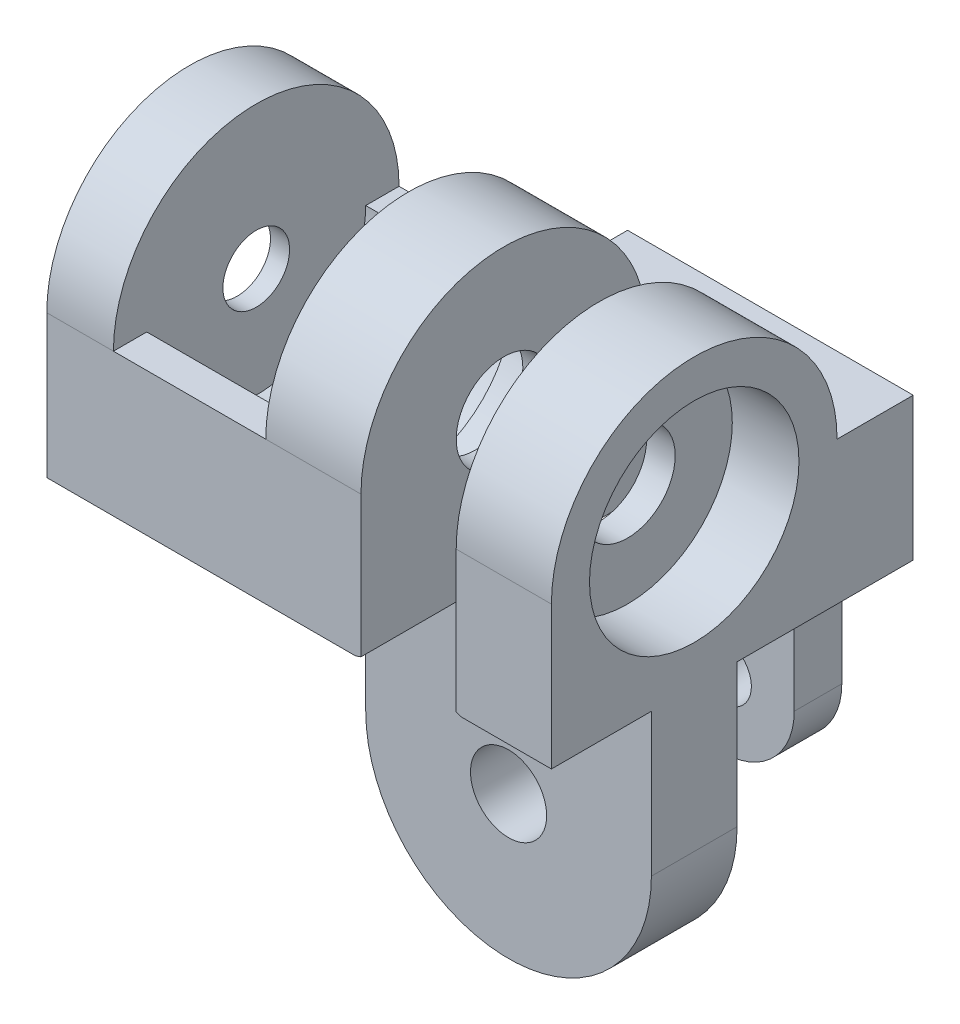
SolidWorks part; units mm, degrees
ref_plane "Front Plane" through (0, 0, 0) normal (0, 0, 1) x (1, 0, 0)
ref_plane "Top Plane" through (0, 0, 0) normal (0, 1, 0) x (1, 0, 0)
ref_plane "Right Plane" through (0, 0, 0) normal (1, 0, 0) x (0, 0, -1)
sketch "Sketch1" plane through (0, 0, 0) normal (0, 1, 0) x (1, 0, 0)
  circle A0 centre (0, 0) radius 15
  dimension "D1" = 30
extrude "Boss-Extrude1" add sketch "Sketch1" along normal blind 30
sketch "Sketch8" plane through (0, 30, 0) normal (0, 1, 0) x (1, 0, 0)
  line L0 (-16.5, 0) -> (16.5, 0) construction
  line L1 (15, 0) -> (-15, 0)
  line L2 (15, 0) -> (15, -15)
  line L3 (15, -15) -> (-15, -15)
  line L4 (-15, 0) -> (-15, -15)
  circle A0 centre (0, 0) radius 15 construction
  dimension "D1" = 15
  dimension "D2" = 30
revolve "Revolve1" add sketch "Sketch8" angle 180 about L1
sketch "Sketch9" plane through (0, 30, 0) normal (0, -1, 0) x (1, 0, 0)
  line L1 (15, 15) -> (-15, 15)
  line L2 (15, 15) -> (15, -15)
  line L3 (15, -15) -> (-15, -15)
  line L4 (-15, 15) -> (-15, -15)
extrude "Boss-Extrude3" add sketch "Sketch9" along normal blind 15
sketch "Sketch10" plane through (15, 0, 0) normal (1, 0, 0) x (0, 0, -1)
  circle A0 centre (0, 30) radius 5
  dimension "D1" = 10
extrude "Cut-Extrude1" cut sketch "Sketch10" against normal blind 30
ref_plane "Plane1" through (5, 0, 0) normal (1, 0, 0) x (0, 0, -1)
sketch "Sketch13" plane through (5, 0, 0) normal (1, 0, 0) x (0, 0, -1)
  line L0 (0, 16.5) -> (0, -16.5) construction
  line L1 (15, 15) -> (0, 15) construction
  circle A0 centre (0, 30) radius 16
  dimension "D1" = 32
  dimension "D2" = 15
extrude "Cut-Extrude2" cut sketch "Sketch13" against normal blind 10
sketch "Sketch14" plane through (0, 0, 15) normal (0, 0, 1) x (1, 0, 0)
  line L0 (5, -16.5) -> (5, 16.5) construction
  line L1 (-5, 30) -> (5, 30)
  line L2 (-5, 30) -> (-5, 15)
  line L3 (-5, 15) -> (5, 15)
  line L4 (5, 30) -> (5, 15)
  line L5 (0, 15) -> (15, 15) construction
extrude "Cut-Extrude3" cut sketch "Sketch14" against normal blind 67
sketch "Sketch15" plane through (-15, 0, 0) normal (-1, 0, 0) x (0, 0, 1)
  circle A0 centre (0, 30) radius 5 construction
  circle A1 centre (0, 30) radius 5
  circle A2 centre (0, 30) radius 11
  dimension "D1" = 22
extrude "Cut-Extrude4" cut sketch "Sketch15" against normal blind 7
sketch "Sketch16" plane through (15, 0, 0) normal (1, 0, 0) x (0, 0, -1)
  circle A0 centre (0, 30) radius 5 construction
  circle A1 centre (0, 30) radius 5
  circle A2 centre (0, 30) radius 11
  dimension "D1" = 22
extrude "Cut-Extrude5" cut sketch "Sketch16" against normal blind 7
ref_plane "Plane2" through (-31, 0, 0) normal (-1, 0, 0) x (0, 0, 1)
sketch "Sketch17" plane through (-31, 0, 0) normal (-1, 0, 0) x (0, 0, 1)
  line L0 (-15, 30) -> (-15, 15)
  line L1 (-15, 15) -> (0, 15)
  line L2 (0, 15) -> (15, 15)
  line L3 (15, 15) -> (15, 30)
  circle A2 centre (0, 30) radius 3.5
  circle A3 centre (0, 30) radius 11 construction
  circle A4 centre (0, 30) radius 8
  circle A5 centre (0, 30) radius 15
  arc A6 (-15, 30) -> (0, 15) centre (0, 30) ccw
  arc A7 (15, 30) -> (0, 15) centre (0, 30) cw
  dimension "D1" = 7
  dimension "D2" = 16
extrude "Boss-Extrude4" add sketch "Sketch17" along normal blind 2 separate body contours A4 A2 | A5 A4 | A5 L0 L1 | A5 L2 L3
sketch "Sketch18" plane through (-33, 0, 0) normal (-1, 0, 0) x (0, 0, 1)
  line L0 (8.5, 30) -> (8.5, 15)
  line L1 (-15, 15) -> (15, 15) construction
  line L2 (8.5, 15) -> (-8.5, 15)
  line L3 (-8.5, 15) -> (-8.5, 30)
  circle A2 centre (0, 30) radius 8.5
  dimension "D1" = 17
extrude "Boss-Extrude5" add sketch "Sketch18" along normal blind 5
sketch "Sketch20" plane through (-15, 0, 0) normal (-1, 0, 0) x (0, 0, 1)
  line L0 (-11.5, 30) -> (-15, 30)
  line L1 (-15, 30) -> (-15, 15)
  line L2 (-15, 15) -> (15, 15)
  line L3 (15, 15) -> (14.1421, 15) construction
  line L4 (-15, 15) -> (-8.5, 15) construction
  line L5 (15, 15) -> (15, 30)
  line L6 (15, 15) -> (15, 30) construction
  line L7 (15, 30) -> (11.5, 30)
  circle A0 centre (0, 30) radius 11.5
  line M4 (-15, 30) -> (-15, 15)
  line M5 (-15, 15) -> (0, 15)
  line M6 (0, 15) -> (15, 15)
  line M7 (15, 15) -> (15, 30)
  dimension "D1" = 23
extrude "Boss-Extrude6" add sketch "Sketch20" along normal blind 16 contours A0 L0 L7 M4 M5 M6 M7
sketch "Sketch21" plane through (0, 15, 0) normal (0, -1, 0) x (1, 0, 0)
  line L1 (15, 15) -> (-38, 15)
  line L2 (15, 15) -> (15, -15)
  line L3 (15, -15) -> (-38, -15)
  line L4 (-38, 15) -> (-38, -15)
extrude "Cut-Extrude7" cut sketch "Sketch21" along normal blind 20
ref_plane "Plane3" through (0, 0, 0) normal (0, -1, 0) x (-1, 0, 0)
sketch "Sketch23" plane through (0, 0, 0) normal (0, -1, 0) x (-1, 0, 0)
  line L0 (-15, -4.5) -> (0, -4.5)
  line L1 (-15, -4.5) -> (-15, 4.5)
  line L2 (0, -4.5) -> (0, 4.5)
  line L3 (-15, 4.5) -> (0, 4.5)
  line L4 (-15, 15) -> (-15, -15) construction
  line L5 (0, 16.5) -> (0, -16.5) construction
  line L6 (-16.5, 0) -> (16.5, 0) construction
  dimension "D1" = 9
  dimension "D2" = 4.5
revolve "Revolve2" add sketch "Sketch23" angle 360 about L2
sketch "Sketch24" plane through (0, 15, 0) normal (0, -1, 0) x (1, 0, 0)
  line L1 (-15, 4.5) -> (15, 4.5)
  line L2 (-15, 4.5) -> (-15, -4.5)
  line L3 (-15, -4.5) -> (15, -4.5)
  line L4 (15, 4.5) -> (15, -4.5)
extrude "Boss-Extrude7" add sketch "Sketch24" along normal blind 15
sketch "Sketch25" plane through (0, 0, 4.5) normal (0, 0, 1) x (1, 0, 0)
  circle A0 centre (0, 0) radius 4
  dimension "D1" = 8
extrude "Cut-Extrude8" cut sketch "Sketch25" against normal blind 15
sketch "Sketch26" plane through (0, 0, -15) normal (0, 0, -1) x (-1, 0, 0)
  line L0 (-16.5, 0) -> (16.5, 0) construction
  line L1 (-15, 30) -> (15, 30)
  line L2 (-15, 30) -> (-15, 15)
  line L3 (-15, 15) -> (-12.5, 15)
  line L4 (15, 30) -> (15, 15)
  line L6 (-7.5, 10) -> (-7.5, 0)
  line L7 (-7.5, 0) -> (7.5, 0)
  line L8 (7.5, 10) -> (7.5, 0)
  line L9 (-5, 15) -> (-15, 15) construction
  line L10 (12.5, 15) -> (15, 15)
  line L11 (38, 15) -> (5, 15) construction
  line L12 (15, 30) -> (15, 45) construction
  circle A0 centre (0, 0) radius 7.5
  circle A1 centre (0, 0) radius 3
  arc A2 (-7.5, 10) -> (-12.5, 15) centre (-12.5, 10) ccw
  arc A3 (12.5, 15) -> (7.5, 10) centre (12.5, 10) ccw
  line M13 (-15, 15) -> (-5, 15)
  line M14 (-5, 15) -> (-5, 30)
  line M15 (-5, 30) -> (-15, 30)
  line M16 (-15, 30) -> (-15, 15)
  dimension "D1" = 6
  dimension "D2" = 15
  dimension "D3" = 5
  dimension "D4" = 5
extrude "Boss-Extrude8" add sketch "Sketch26" along normal blind 5 from offset 3 contours M16 M13 M14 M15 | A3 L10 L4 L1 A2 L6 A0 L8 M14 M13 | A1 L7 A0 | A1 L7 A0
sketch "Sketch30" plane through (0, 0, -18) normal (0, 0, 1) x (1, 0, 0)
  line L1 (15, 30) -> (-15, 30)
  line L2 (15, 30) -> (15, 15)
  line L3 (15, 15) -> (-15, 15)
  line L4 (-15, 30) -> (-15, 15)
  point P5 (0, 0)
extrude "Boss-Extrude9" add sketch "Sketch30" along normal blind 3
sketch "Sketch27" plane through (0, 0, 4.5) normal (0, 0, 1) x (1, 0, 0)
  circle A0 centre (0, 0) radius 16
  dimension "D1" = 32
extrude "Cut-Extrude9" cut sketch "Sketch27" along normal blind 16
sketch "Sketch28" plane through (0, 0, -4.5) normal (0, 0, -1) x (-1, 0, 0)
  circle A0 centre (0, 0) radius 16
  dimension "D1" = 32
extrude "Cut-Extrude10" cut sketch "Sketch28" along normal blind 10.5
sketch "Sketch29" plane through (5, 0, 0) normal (-1, 0, 0) x (0, 0, 1)
  line L0 (0, -29.15) -> (0, 29.15) construction
  circle A0 centre (0, 30) radius 16
  arc A1 (15, 30) -> (-15, 30) centre (0, 30) ccw construction
  dimension "D1" = 32
extrude "Cut-Extrude12" cut sketch "Sketch29" along normal blind 10
